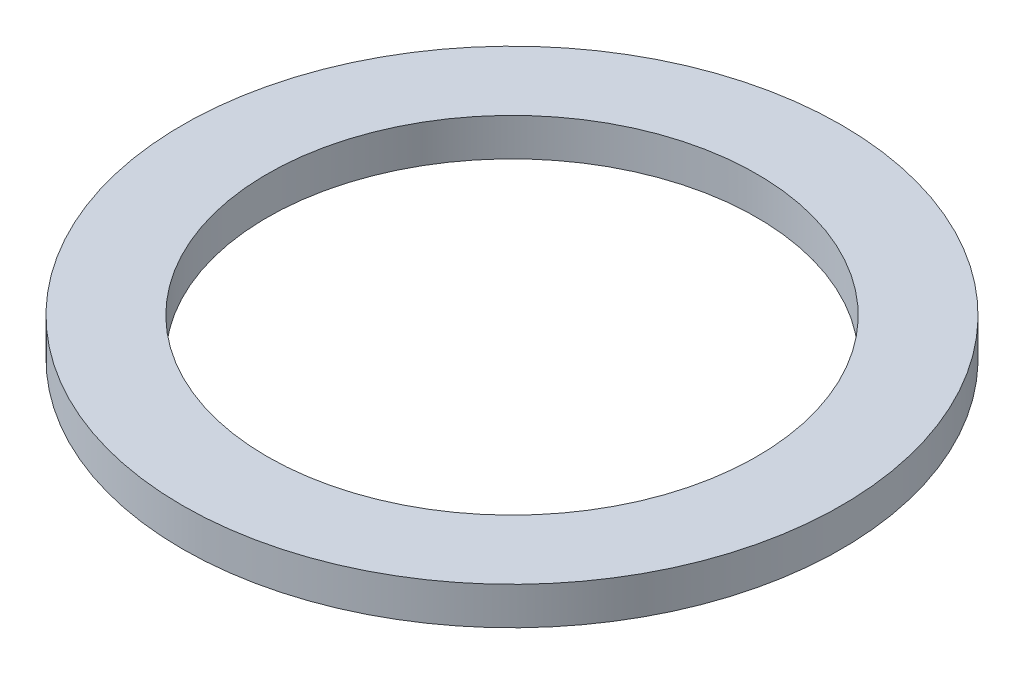
SolidWorks part; units mm, degrees
ref_plane "Front Plane" through (0, 0, 0) normal (0, 0, 1) x (1, 0, 0)
ref_plane "Top Plane" through (0, 0, 0) normal (0, 1, 0) x (1, 0, 0)
ref_plane "Right Plane" through (0, 0, 0) normal (1, 0, 0) x (0, 0, -1)
sketch "Sketch1" plane through (0, 0, 0) normal (0, 1, 0) x (1, 0, 0)
  circle A0 centre (0, 0) radius 5.2
  circle A1 centre (0, 0) radius 7
  dimension "D1" = 10.4
  dimension "D2" = 14
extrude "Boss-Extrude1" add sketch "Sketch1" along normal blind 0.8
